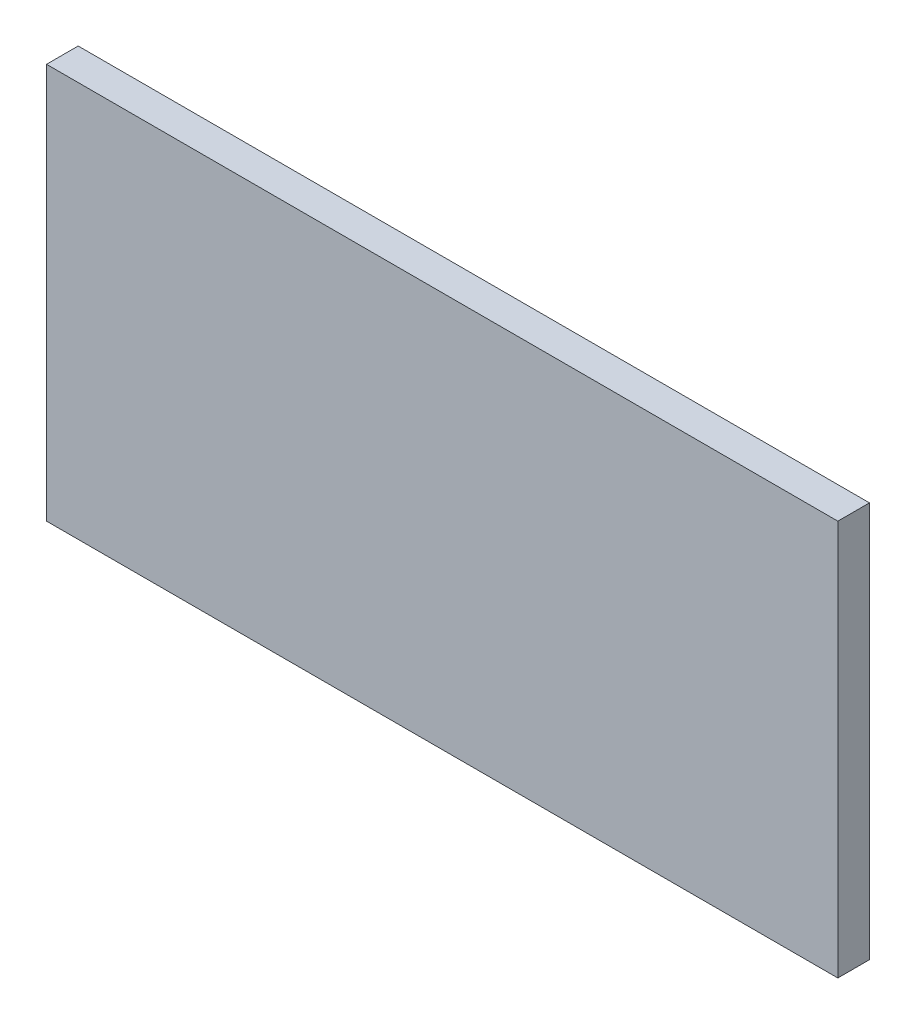
SolidWorks part; units mm, degrees
ref_plane "前视基准面" through (0, 0, 0) normal (0, 0, 1) x (1, 0, 0)
ref_plane "上视基准面" through (0, 0, 0) normal (0, 1, 0) x (1, 0, 0)
ref_plane "右视基准面" through (0, 0, 0) normal (1, 0, 0) x (0, 0, -1)
other "Configuration Table"
sketch "草图1" plane through (0, 0, 0) normal (0, 0, 1) x (1, 0, 0)
  line L1 (-55.5651, 30.0895) -> (-5.5651, 30.0895)
  line L2 (-55.5651, 30.0895) -> (-55.5651, 5.0895)
  line L3 (-55.5651, 5.0895) -> (-5.5651, 5.0895)
  line L4 (-5.5651, 30.0895) -> (-5.5651, 5.0895)
  line L5 (-55.5651, 30.0895) -> (-5.5651, 5.0895) construction
  line L6 (-55.5651, 5.0895) -> (-5.5651, 30.0895) construction
  point P0 (-30.5651, 17.5895)
  dimension "D1" = 25
  dimension "D2" = 50
extrude "凸台-拉伸1" add sketch "草图1" along normal blind 2
